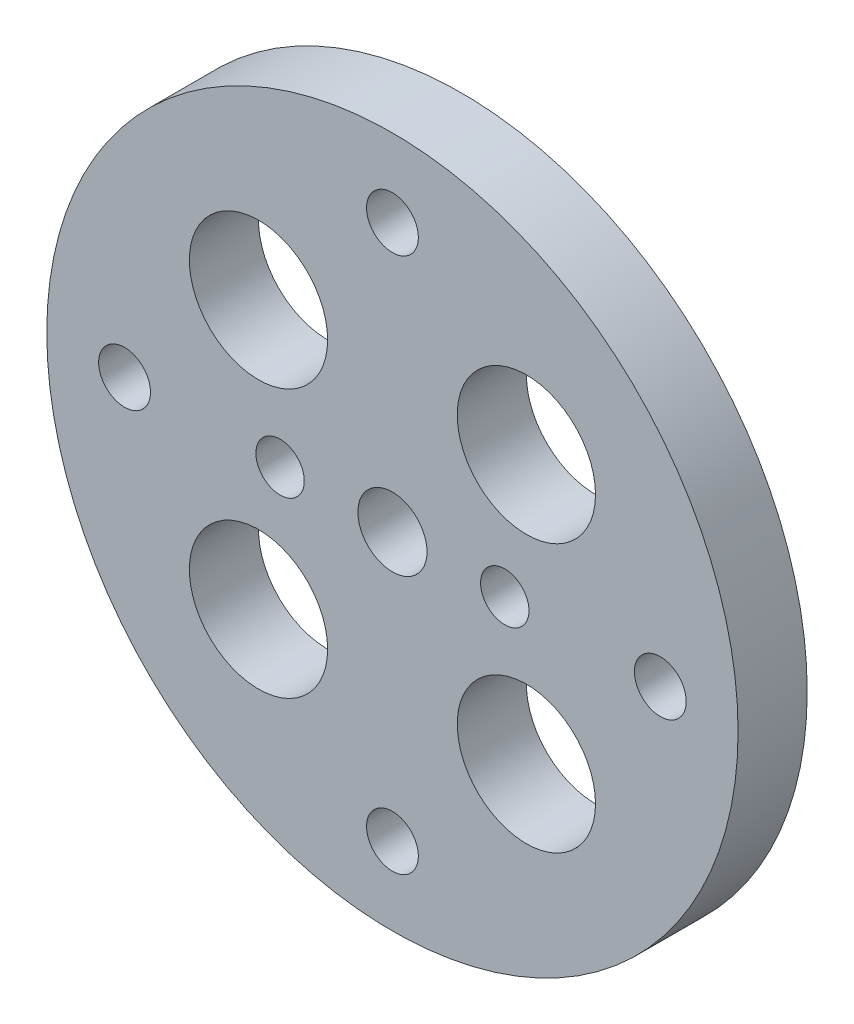
SolidWorks part; units mm, degrees
ref_plane "前视基准面" through (0, 0, 0) normal (0, 0, 1) x (1, 0, 0)
ref_plane "上视基准面" through (0, 0, 0) normal (0, 1, 0) x (1, 0, 0)
ref_plane "右视基准面" through (0, 0, 0) normal (1, 0, 0) x (0, 0, -1)
sketch "草图1" plane through (0, 0, 0) normal (0, 0, 1) x (1, 0, 0)
  line L0 (0, 0) -> (6.5, 0) construction
  line L1 (0, 0) -> (0, 3.8526) construction
  line L2 (-15.5, 0) -> (0, 15.5) construction
  circle A0 centre (0, 0) radius 15.5 construction
  circle A1 centre (0, 0) radius 20
  circle A2 centre (0, 0) radius 2
  circle A3 centre (6.5, 0) radius 1.4
  circle A4 centre (0, -15.5) radius 1.5
  circle A5 centre (-15.5, 0) radius 1.5
  circle A6 centre (0, 15.5) radius 1.5
  circle A7 centre (15.5, 0) radius 1.5
  circle A8 centre (-6.5, 0) radius 1.4
  circle A9 centre (-7.75, 7.75) radius 4
  circle A10 centre (7.75, 7.75) radius 4
  circle A11 centre (7.75, -7.75) radius 4
  circle A12 centre (-7.75, -7.75) radius 4
  dimension "D1" = 31
  dimension "D2" = 4
  dimension "D3" = 2.8
  dimension "D4" = 3
  dimension "D6" = 40
  dimension "D8" = 8
  dimension "D7" = 6.5
  dimension "D5" = 4
  dimension "D9" = 4
extrude "凸台-拉伸1" add sketch "草图1" along normal blind 4
